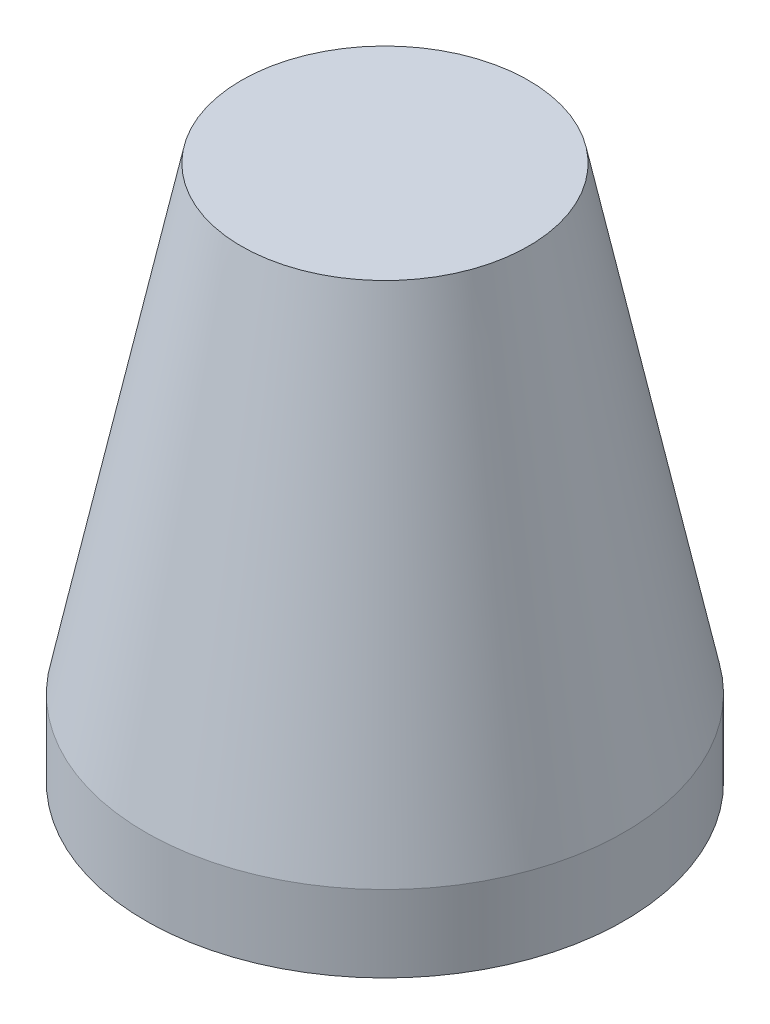
SolidWorks part; units mm, degrees
ref_plane "前视基准面" through (0, 0, 0) normal (0, 0, 1) x (1, 0, 0)
ref_plane "上视基准面" through (0, 0, 0) normal (0, 1, 0) x (1, 0, 0)
ref_plane "右视基准面" through (0, 0, 0) normal (1, 0, 0) x (0, 0, -1)
other "Configuration Table"
sketch "草图1" plane through (0, 0, 0) normal (0, 0, 1) x (1, 0, 0)
  line L0 (0, 0) -> (-25, 0)
  line L1 (-25, 0) -> (-25, 8)
  line L2 (-25, 8) -> (-15, 56)
  line L3 (-15, 56) -> (0, 56)
  line L4 (0, 56) -> (0, 0)
  dimension "D1" = 25
  dimension "D2" = 15
  dimension "D3" = 8
  dimension "D4" = 56
revolve "旋转1" add sketch "草图1" angle 360 about L4
